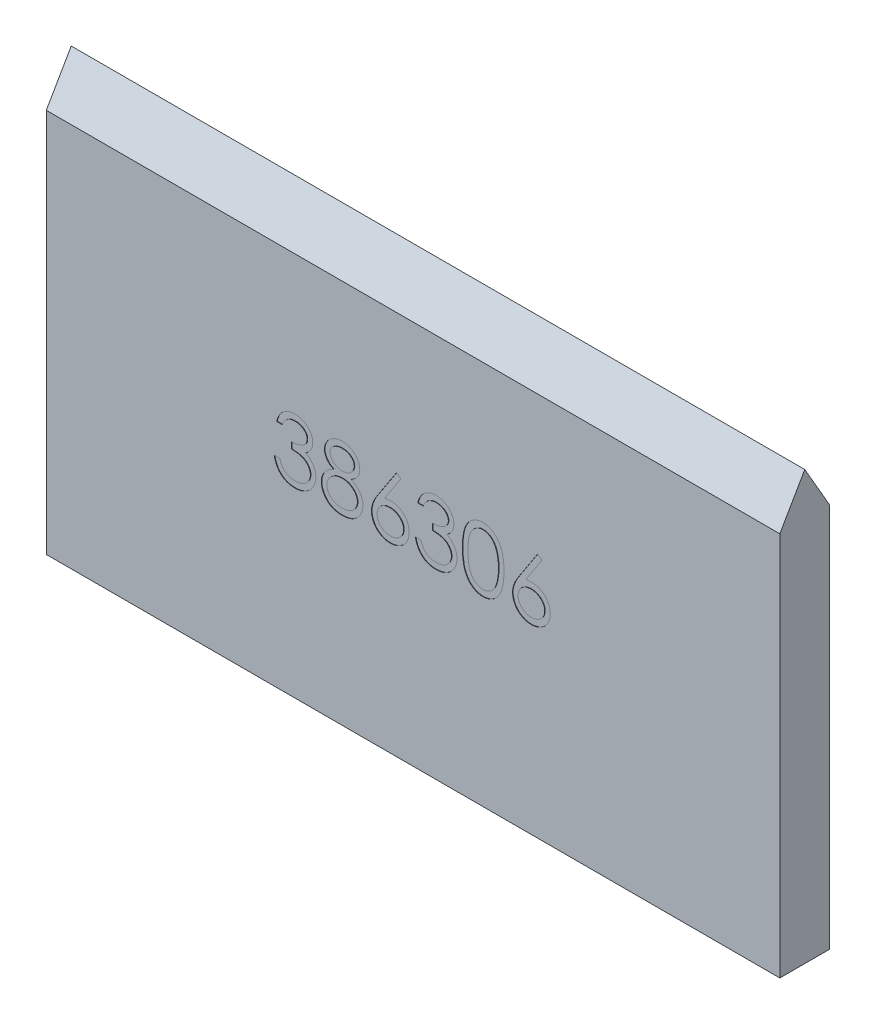
SolidWorks part; units mm, degrees
material "D2"
ref_plane "Alzado" through (0, 0, 0) normal (0, 0, 1) x (1, 0, 0)
ref_plane "Planta" through (0, 0, 0) normal (0, 1, 0) x (1, 0, 0)
ref_plane "Vista lateral" through (0, 0, 0) normal (1, 0, 0) x (0, 0, -1)
sketch "Croquis1" plane through (0, 0, 0) normal (0, 0, 1) x (1, 0, 0)
  line L0 (-19.05, 0) -> (0, 0) construction
  line L1 (-19.05, 11.1125) -> (19.05, 11.1125)
  line L2 (-19.05, 11.1125) -> (-19.05, -11.1125)
  line L3 (-19.05, -11.1125) -> (19.05, -11.1125)
  line L4 (19.05, 11.1125) -> (19.05, -11.1125)
  line L5 (0, 0) -> (0, 11.1125) construction
  dimension "D1" = 38.1
  dimension "D2" = 22.225
extrude "Saliente-Extruir1" add sketch "Croquis1" along normal mid plane 2.5908
sketch "Croquis2" plane through (19.05, 0, 0) normal (1, 0, 0) x (0, 0, -1)
  line L0 (-1.2954, 8.8688) -> (0, 11.1125)
  line L1 (-1.2954, -11.1125) -> (-1.2954, 11.1125) construction
  line L2 (-1.2954, 11.1125) -> (1.2954, 11.1125) construction
  line L3 (0, 11.1125) -> (-1.2954, 11.1125)
  line L4 (-1.2954, 11.1125) -> (-1.2954, 8.8688)
  dimension "D1" = 60
extrude "Cortar-Extruir1" cut sketch "Croquis2" against normal through all
mirror "Simetría1" about plane through (0, 0, 0) normal (0, 0, 1) of "Cortar-Extruir1"
sketch "Croquis3" plane through (0, 0, 1.2954) normal (0, 0, 1) x (1, 0, 0)
  line L0 (-12.7, -1.5875) -> (12.7, -1.5875) construction
  line L1 (0, -1.5875) -> (0, -11.1125) construction
  line L2 (-19.05, -11.1125) -> (19.05, -11.1125) construction
  text T0 "386306" font "Century Gothic" height 3.175
  dimension "D1" = 9.525
  dimension "D2" = 25.4
extrude "Cortar-Extruir2" cut sketch "Croquis3" against normal blind 0.0254
